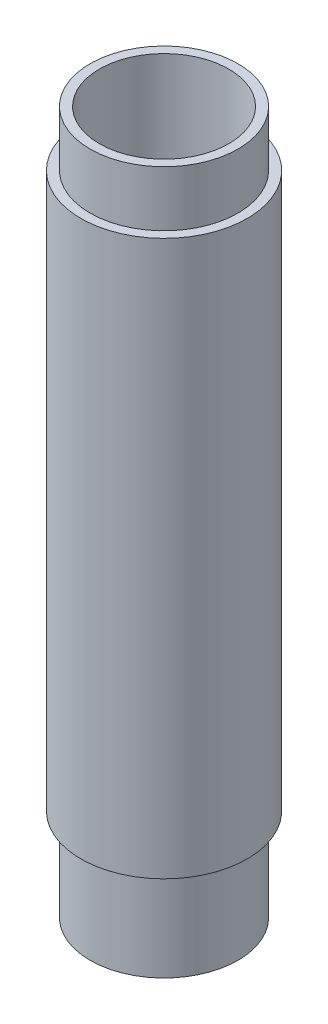
SolidWorks part; units mm, degrees
ref_plane "Front Plane" through (0, 0, 0) normal (0, 0, 1) x (1, 0, 0)
ref_plane "Top Plane" through (0, 0, 0) normal (0, 1, 0) x (1, 0, 0)
ref_plane "Right Plane" through (0, 0, 0) normal (1, 0, 0) x (0, 0, -1)
sketch "Sketch2" plane through (0, 0, 0) normal (0, 1, 0) x (1, 0, 0)
  circle A0 centre (0, 0) radius 8
  circle A1 centre (0, 0) radius 7
ref_plane "Plane1" through (0, 10, 0) normal (0, 1, 0) x (1, 0, 0)
sketch "Sketch3" plane through (0, 10, 0) normal (0, 1, 0) x (1, 0, 0)
  circle A0 centre (0, 0) radius 8
  circle A1 centre (0, 0) radius 9
extrude "Boss-Extrude3" add sketch "Sketch2" along normal blind 15
ref_plane "Plane2" through (0, 45, 0) normal (0, 1, 0) x (1, 0, 0)
sketch "Sketch4" plane through (0, 45, 0) normal (0, 1, 0) x (1, 0, 0)
  circle A0 centre (0, 0) radius 7
  circle A1 centre (0, 0) radius 8
extrude "Boss-Extrude6" add sketch "Sketch4" along normal blind 11 and the other way blind 40
extrude "Boss-Extrude7" add sketch "Sketch3" along normal blind 60
sketch "Sketch6" plane through (0, 45, 0) normal (0, 1, 0) x (1, 0, 0)
  circle A0 centre (0, 0) radius 7
  circle A1 centre (0, 0) radius 8
extrude "Boss-Extrude8" add sketch "Sketch6" along normal blind 31
